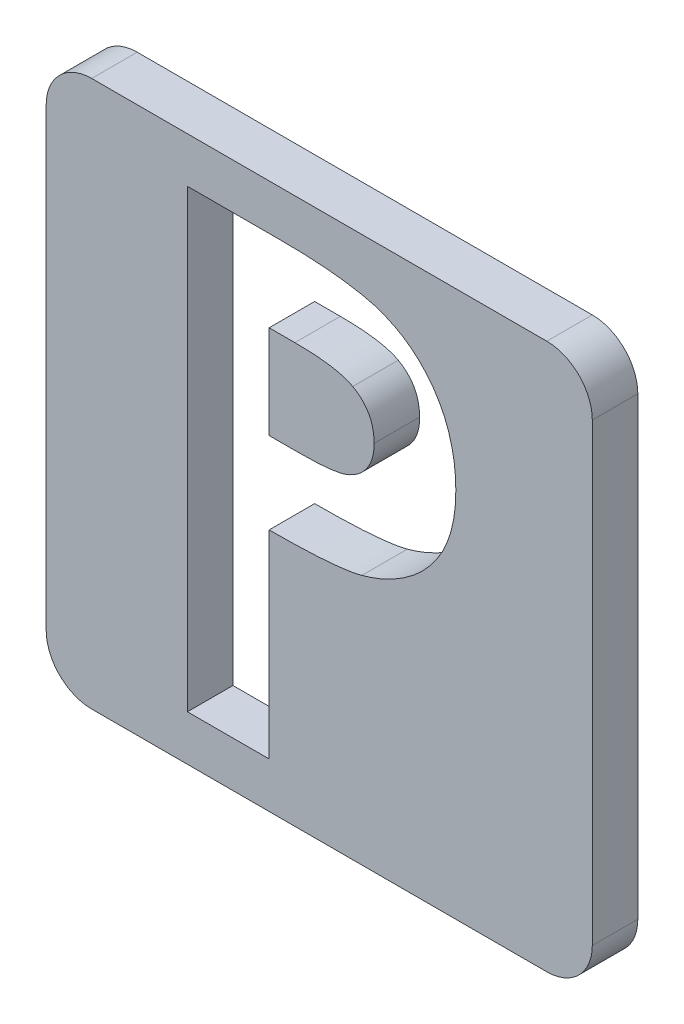
SolidWorks part; units mm, degrees
ref_plane "Front Plane" through (0, 0, 0) normal (0, 0, 1) x (1, 0, 0)
ref_plane "Top Plane" through (0, 0, 0) normal (0, 1, 0) x (1, 0, 0)
ref_plane "Right Plane" through (0, 0, 0) normal (1, 0, 0) x (0, 0, -1)
sketch "Sketch1" plane through (0, 0, 0) normal (0, 0, 1) x (1, 0, 0)
  line L1 (-50, 60) -> (50, 60)
  line L2 (-60, 50) -> (-60, -50)
  line L3 (-50, -60) -> (50, -60)
  line L4 (60, 50) -> (60, -50)
  line L5 (-60, 60) -> (60, -60) construction
  line L6 (-60, -60) -> (60, 60) construction
  arc A0 (-60, -50) -> (-50, -60) centre (-50, -50) ccw
  arc A1 (50, -60) -> (60, -50) centre (50, -50) ccw
  arc A2 (50, 60) -> (60, 50) centre (50, 50) cw
  arc A3 (-50, 60) -> (-60, 50) centre (-50, 50) ccw
  point P0 (0, 0)
  dimension "D3" = 10
  dimension "D1" = 120
  dimension "D2" = 120
extrude "Boss-Extrude1" add sketch "Sketch1" along normal blind 10 contours A3 L2 A0 L3 A1 L4 A2 L1
sketch "Sketch2" plane through (0, 0, 10) normal (0, 0, 1) x (1, 0, 0)
  line L0 (0, 0) -> (0, 40) construction
  line L1 (-50, 50) -> (50, 50) construction
  line L2 (-50, 50) -> (-50, -50) construction
  line L3 (-50, -50) -> (50, -50) construction
  line L4 (50, 50) -> (50, -50) construction
  line L5 (-50, 50) -> (50, -50) construction
  line L6 (-50, -50) -> (50, 50) construction
  line L7 (0, 40) -> (-40, 40) construction
  line L8 (-40, 40) -> (-40, 0) construction
  line L9 (-40, 0) -> (0, 0) construction
  line L11 (0, 20) -> (-20, 20) construction
  line L12 (-20, 40) -> (-20, 20) construction
  circle A0 centre (0, 40) radius 4 construction
  circle A1 centre (0, 20) radius 4 construction
  circle A2 centre (0, 0) radius 4 construction
  circle A3 centre (-20, 20) radius 4 construction
  circle A4 centre (-20, 40) radius 4 construction
  circle A5 centre (-40, 40) radius 4 construction
  circle A6 centre (0, 0) radius 4 construction
  circle A7 centre (20, 0) radius 4 construction
  circle A8 centre (40, 0) radius 4 construction
  circle A9 centre (40, 20) radius 4 construction
  circle A10 centre (40, 40) radius 4 construction
  circle A11 centre (20, 20) radius 4 construction
  circle A12 centre (0, 0) radius 4 construction
  circle A13 centre (0, -20) radius 4 construction
  circle A14 centre (0, -40) radius 4 construction
  circle A15 centre (20, -40) radius 4 construction
  circle A16 centre (40, -40) radius 4 construction
  circle A17 centre (20, -20) radius 4 construction
  circle A18 centre (0, 0) radius 4 construction
  circle A19 centre (-20, 0) radius 4 construction
  circle A20 centre (-40, 0) radius 4 construction
  circle A21 centre (-40, -20) radius 4 construction
  circle A22 centre (-40, -40) radius 4 construction
  circle A23 centre (-20, -20) radius 4 construction
  text T0 "P" font "Century Gothic" height 100
  point P0 (0, 0)
  point P55 (0, 0)
  dimension "D4" = 8
  dimension "D1" = 100
  dimension "D2" = 100
  dimension "D3" = 40
  dimension "D5" = 4
extrude "Cut-Extrude29" cut sketch "Sketch2" against normal blind 10
